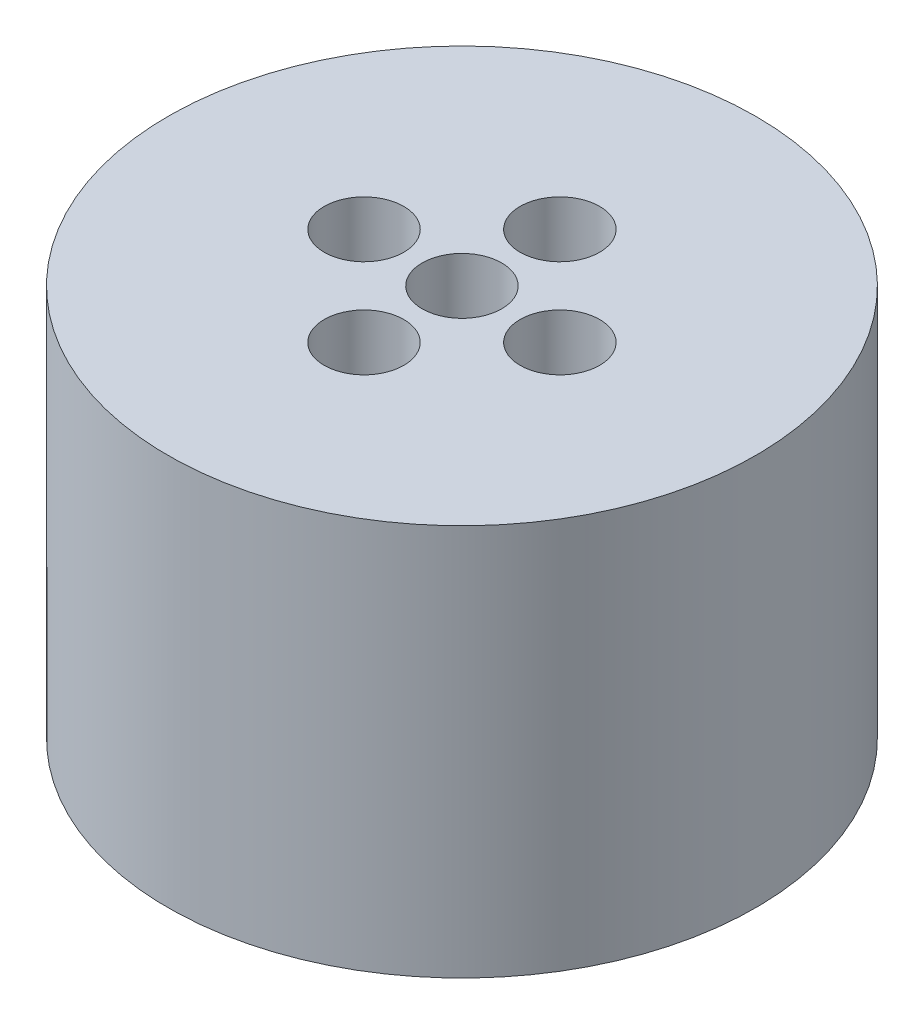
SolidWorks part; units mm, degrees
ref_plane "Alzado" through (0, 0, 0) normal (0, 0, 1) x (1, 0, 0)
ref_plane "Planta" through (0, 0, 0) normal (0, 1, 0) x (1, 0, 0)
ref_plane "Vista lateral" through (0, 0, 0) normal (1, 0, 0) x (0, 0, -1)
sketch "Croquis1" plane through (0, 0, 0) normal (0, 1, 0) x (1, 0, 0)
  circle A0 centre (0, 0) radius 12
  circle A1 centre (0, 0) radius 11
  circle A2 centre (0, 0) radius 1.625
  dimension "D1" = 22
  dimension "D2" = 1
  dimension "D3" = 3.25
extrude "Saliente-Extruir1" add sketch "Croquis1" along normal blind 13 contours A0 A1
sketch "Croquis3" plane through (0, 13, 0) normal (0, 1, 0) x (1, 0, 0)
  circle A0 centre (0, 0) radius 12
  circle A1 centre (0, 0) radius 1.625
  circle A2 centre (0, 4) radius 1.625
  circle A3 centre (4, 0) radius 1.625
  circle A4 centre (0, -4) radius 1.625
  circle A5 centre (-4, 0) radius 1.625
  circle A6 centre (0, 0) radius 12 construction
  dimension "D1" = 3.25
  dimension "D2" = 3.25
  dimension "D3" = 4
  dimension "D4" = 4
extrude "Saliente-Extruir2" add sketch "Croquis3" along normal blind 3
